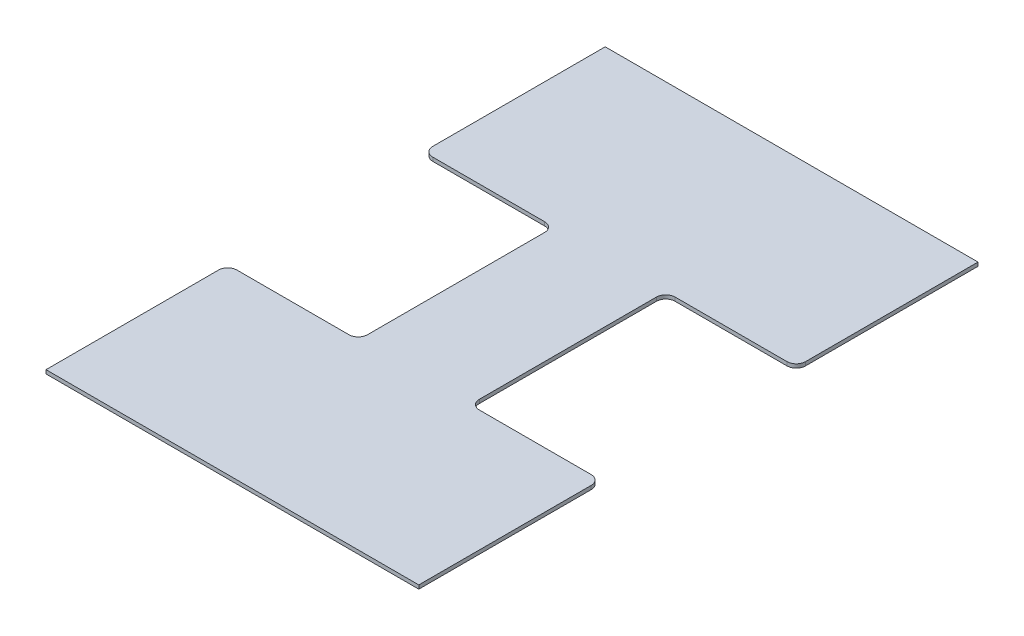
SolidWorks part; units mm, degrees
material "1023 碳钢板 (SS)"
ref_plane "前视基准面" through (0, 0, 0) normal (0, 0, 1) x (1, 0, 0)
ref_plane "上视基准面" through (0, 0, 0) normal (0, 1, 0) x (1, 0, 0)
ref_plane "右视基准面" through (0, 0, 0) normal (1, 0, 0) x (0, 0, -1)
sketch "草图1" plane through (0, 0, 0) normal (0, 1, 0) x (1, 0, 0)
  line L1 (-200, -300) -> (200, -300)
  line L2 (-200, -300) -> (-200, 300)
  line L3 (-200, 300) -> (200, 300)
  line L4 (200, -300) -> (200, 300)
  line L5 (-200, -300) -> (200, 300) construction
  line L6 (-200, 300) -> (200, -300) construction
  point P0 (0, 0)
  dimension "D1" = 400
  dimension "D2" = 600
extrude "凸台-拉伸1" add sketch "草图1" along normal blind 4
sketch "草图2" plane through (0, 4, 0) normal (0, 1, 0) x (1, 0, 0)
  line L0 (0, 0) -> (-588.7967, 0) construction
  line L1 (-200, 300) -> (-200, -300) construction
  line L2 (-200, -105) -> (-60, -105)
  line L3 (-200, -105) -> (-200, 105)
  line L4 (-200, 105) -> (-60, 105)
  line L5 (-60, -105) -> (-60, 105)
  line L6 (-200, -105) -> (-60, 105) construction
  line L7 (-200, 105) -> (-60, -105) construction
  point P3 (-130, 0)
  dimension "D1" = 210
  dimension "45" = 140
extrude "切除-拉伸3" cut sketch "草图2" against normal through all
mirror "镜向1" about plane through (0, 0, 0) normal (1, 0, 0) of "切除-拉伸3"
fillet "圆角1" radius 10 8 edges at (-200, 2, 105) (-200, 2, -105) (-60, 2, 105) (-60, 2, -105) (200, 2, -105) (200, 2, 105) (60, 2, 105) (60, 2, -105)
